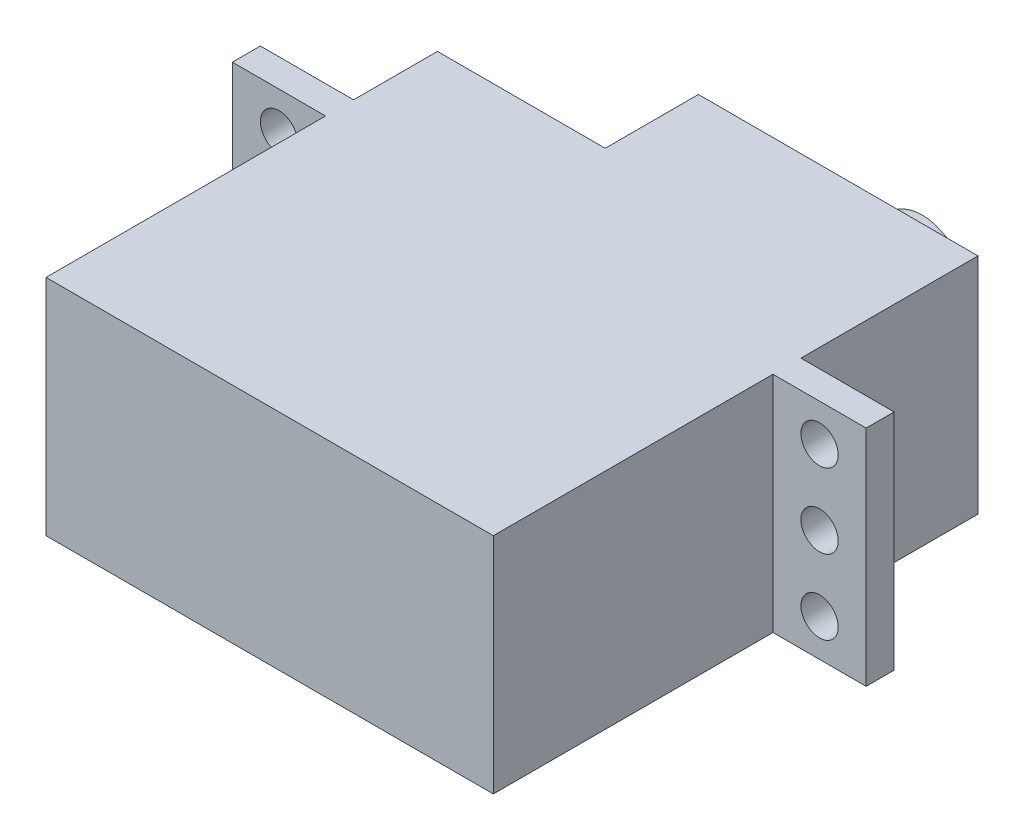
SolidWorks part; units mm, degrees
ref_plane "Front Plane" through (0, 0, 0) normal (0, 0, 1) x (1, 0, 0)
ref_plane "Top Plane" through (0, 0, 0) normal (0, 1, 0) x (1, 0, 0)
ref_plane "Right Plane" through (0, 0, 0) normal (1, 0, 0) x (0, 0, -1)
sketch "Sketch1" plane through (0, 0, 0) normal (0, 0, 1) x (1, 0, 0)
  line L1 (0, 0) -> (24, 0)
  line L2 (0, 0) -> (0, -12)
  line L3 (0, -12) -> (24, -12)
  line L4 (24, 0) -> (24, -12)
  dimension "D1" = 24
  dimension "D2" = 12
extrude "Boss-Extrude1" add sketch "Sketch1" along normal blind 21
ref_plane "Plane1" through (0, 0, 6) normal (0, 0, 1) x (1, 0, 0)
sketch "Sketch2" plane through (0, 0, 6) normal (0, 0, 1) x (1, 0, 0)
  line L0 (0, -12) -> (24, -12) construction
  line L1 (-5, 0) -> (29, 0)
  line L2 (-5, 0) -> (-5, -12)
  line L3 (-5, -12) -> (29, -12)
  line L4 (29, 0) -> (29, -12)
  line L5 (24, 0) -> (0, 0) construction
  line L6 (0, 0) -> (0, -12) construction
  line L7 (24, -12) -> (24, 0) construction
  line L8 (-3.5, -2) -> (-5, -2) construction
  line L9 (-1.5, -2) -> (0, -2) construction
  line L10 (-2.5, -1) -> (-2.5, 0) construction
  line L11 (27.5, -2) -> (29, -2) construction
  circle A0 centre (-2.5, -2) radius 1
  circle A1 centre (26.5, -2) radius 1
  circle A2 centre (26.5, -6) radius 1
  circle A3 centre (26.5, -10) radius 1
  circle A4 centre (-2.5, -6) radius 1
  circle A5 centre (-2.5, -10) radius 1
  dimension "D3" = 2
  dimension "D1" = 5
  dimension "D2" = 5
  dimension "D4" = 1
  dimension "D5" = 2
  dimension "D6" = 3
extrude "Boss-Extrude2" add sketch "Sketch2" against normal blind 1.5
sketch "Sketch3" plane through (0, 0, 0) normal (0, 0, -1) x (-1, 0, 0)
  line L0 (0, -12) -> (-24, -12) construction
  line L1 (-24, 0) -> (-9, 0)
  line L2 (-24, 0) -> (-24, -12)
  line L3 (-24, -12) -> (-9, -12)
  line L4 (-9, 0) -> (-9, -12)
  dimension "D1" = 15
extrude "Boss-Extrude3" add sketch "Sketch3" along normal blind 5
sketch "Sketch4" plane through (0, 0, -5) normal (0, 0, -1) x (-1, 0, 0)
  line L0 (-24, -12) -> (-24, 0) construction
  line L1 (-17, -3.6) -> (-17, 0) construction
  line L3 (-17, -8.4) -> (-17, -12) construction
  line L4 (-24, -12) -> (-9, -12) construction
  line L5 (-9, 0) -> (-24, 0) construction
  circle A0 centre (-17, -6) radius 2.4
  dimension "D1" = 4.8
  dimension "D2" = 7
extrude "Boss-Extrude4" add sketch "Sketch4" along normal blind 4
